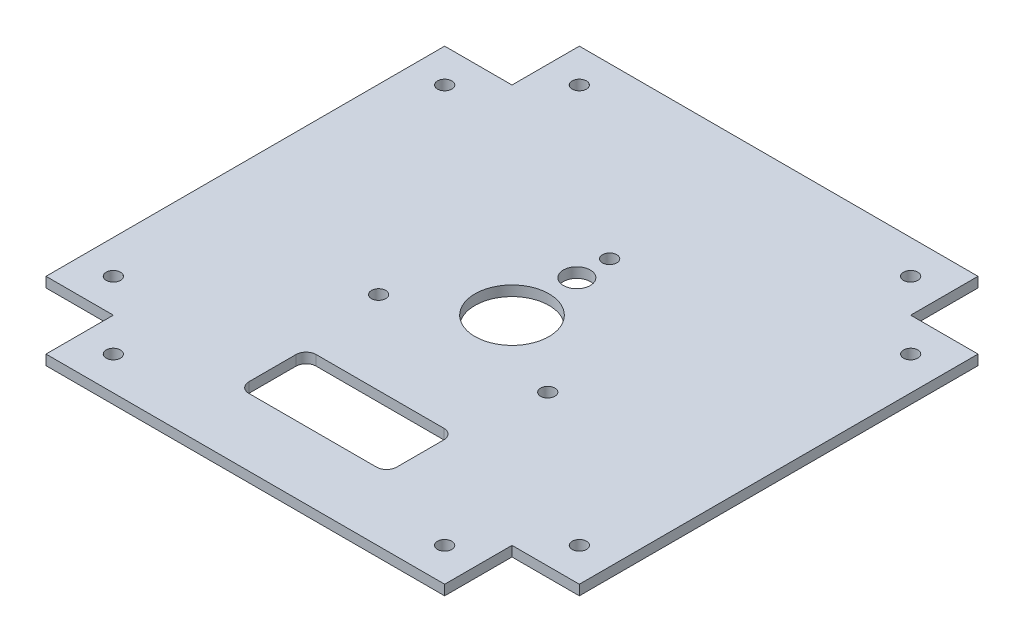
SolidWorks part; units mm, degrees
ref_plane "Front Plane" through (0, 0, 0) normal (0, 0, 1) x (1, 0, 0)
ref_plane "Top Plane" through (0, 0, 0) normal (0, 1, 0) x (1, 0, 0)
ref_plane "Right Plane" through (0, 0, 0) normal (1, 0, 0) x (0, 0, -1)
sketch "Sketch1" plane through (0, 0, 0) normal (0, 1, 0) x (1, 0, 0)
  line L1 (-79.2, -79.2) -> (79.2, -79.2)
  line L2 (-79.2, -79.2) -> (-79.2, 79.2)
  line L3 (-79.2, 79.2) -> (79.2, 79.2)
  line L4 (79.2, -79.2) -> (79.2, 79.2)
  line L5 (-79.2, -79.2) -> (79.2, 79.2) construction
  line L6 (-79.2, 79.2) -> (79.2, -79.2) construction
  point P0 (0, 0)
  dimension "D1" = 158.4
  dimension "D2" = 158.4
extrude "Boss-Extrude1" add sketch "Sketch1" along normal blind 3
sketch "Sketch2" plane through (0, 3, 0) normal (0, 1, 0) x (1, 0, 0)
  line L0 (79.2, 79.2) -> (59.2, 79.2) construction
  line L1 (-79.2, 79.2) -> (-59.2, 79.2) construction
  line L2 (-79.2, 79.2) -> (-79.2, 59.2) construction
  line L3 (-79.2, 59.2) -> (-59.2, 59.2) construction
  line L4 (-59.2, 79.2) -> (-59.2, 59.2) construction
  line L5 (79.2, 79.2) -> (79.2, 59.2) construction
  line L6 (79.2, 59.2) -> (59.2, 59.2) construction
  line L7 (59.2, 79.2) -> (59.2, 59.2) construction
  line L8 (79.2, -79.2) -> (79.2, -59.2) construction
  line L9 (79.2, -79.2) -> (59.2, -79.2) construction
  line L10 (59.2, -79.2) -> (59.2, -59.2) construction
  line L11 (79.2, -59.2) -> (59.2, -59.2) construction
  line L12 (-79.2, -79.2) -> (-59.2, -79.2) construction
  line L13 (-79.2, -79.2) -> (-79.2, -59.2) construction
  line L14 (-79.2, -59.2) -> (-59.2, -59.2) construction
  line L15 (-59.2, -79.2) -> (-59.2, -59.2) construction
  line L16 (-69.2, -79.2) -> (-69.2, 79.2) construction
  line L17 (-79.2, 0) -> (79.2, 0) construction
  line L18 (-79.2, 79.2) -> (-79.2, -79.2) construction
  line L19 (79.2, -79.2) -> (79.2, 79.2) construction
  line L25 (-21.956, -59.2) -> (21.956, -59.2)
  line L26 (-21.956, -59.2) -> (-21.956, -39.2)
  line L27 (-21.956, -39.2) -> (21.956, -39.2)
  line L28 (21.956, -59.2) -> (21.956, -39.2)
  line L29 (-21.956, -59.2) -> (21.956, -39.2) construction
  line L30 (-21.956, -39.2) -> (21.956, -59.2) construction
  circle A0 centre (-69.2, -49.2) radius 2.125
  circle A1 centre (-69.2, 49.2) radius 2.125
  circle A2 centre (-49.2, 69.2) radius 2.125
  circle A3 centre (49.2, 69.2) radius 2.125
  circle A4 centre (69.2, 49.2) radius 2.125
  circle A5 centre (69.2, -49.2) radius 2.125
  circle A6 centre (49.2, -69.2) radius 2.125
  circle A7 centre (-49.2, -69.2) radius 2.125
  circle A8 centre (0, 0) radius 11
  circle A9 centre (0, 29) radius 2.125
  circle A10 centre (25.1147, -14.5) radius 2.125
  circle A11 centre (-25.1147, -14.5) radius 2.125
  circle A12 centre (0, 19.25) radius 4
  circle A13 centre (0, 0) radius 34 construction
  point P44 (0, 0)
  point P53 (0, 0)
  point P55 (0, -49.2)
  point P60 (0, -40.7394)
  dimension "D4" = 4.25
  dimension "D7" = 22
  dimension "D8" = 4.25
  dimension "D12" = 8
  dimension "D13" = 68
  dimension "D1" = 20
  dimension "D2" = 20
  dimension "D5" = 10
  dimension "D9" = 29
  dimension "D11" = 9.75
  dimension "D14" = 20
  dimension "D15" = 10
  dimension "D3" = 4
  dimension "D6" = 4
  dimension "D10" = 3
extrude "Cut-Extrude3" cut sketch "Sketch2" against normal through all
sketch "Sketch3" plane through (0, 3, 0) normal (0, 1, 0) x (1, 0, 0)
  line L0 (79.2, 79.2) -> (59.2, 79.2)
  line L1 (-79.2, 79.2) -> (-59.2, 79.2)
  line L2 (-79.2, 79.2) -> (-79.2, 59.2)
  line L3 (-79.2, 59.2) -> (-59.2, 59.2)
  line L4 (-59.2, 79.2) -> (-59.2, 59.2)
  line L5 (79.2, 79.2) -> (79.2, 59.2)
  line L6 (79.2, 59.2) -> (59.2, 59.2)
  line L7 (59.2, 79.2) -> (59.2, 59.2)
  line L8 (79.2, -79.2) -> (79.2, -59.2)
  line L9 (79.2, -79.2) -> (59.2, -79.2)
  line L10 (59.2, -79.2) -> (59.2, -59.2)
  line L11 (79.2, -59.2) -> (59.2, -59.2)
  line L12 (-79.2, -79.2) -> (-59.2, -79.2)
  line L13 (-79.2, -79.2) -> (-79.2, -59.2)
  line L14 (-79.2, -59.2) -> (-59.2, -59.2)
  line L15 (-59.2, -79.2) -> (-59.2, -59.2)
  point P20 (0, 0)
  dimension "D1" = 20
  dimension "D2" = 20
  dimension "D3" = 4
extrude "Cut-Extrude4" cut sketch "Sketch3" against normal through all
fillet "Fillet1" radius 3 4 edges at (-21.956, 1.5, 59.2) (21.956, 1.5, 59.2) (21.956, 1.5, 39.2) (-21.956, 1.5, 39.2)
